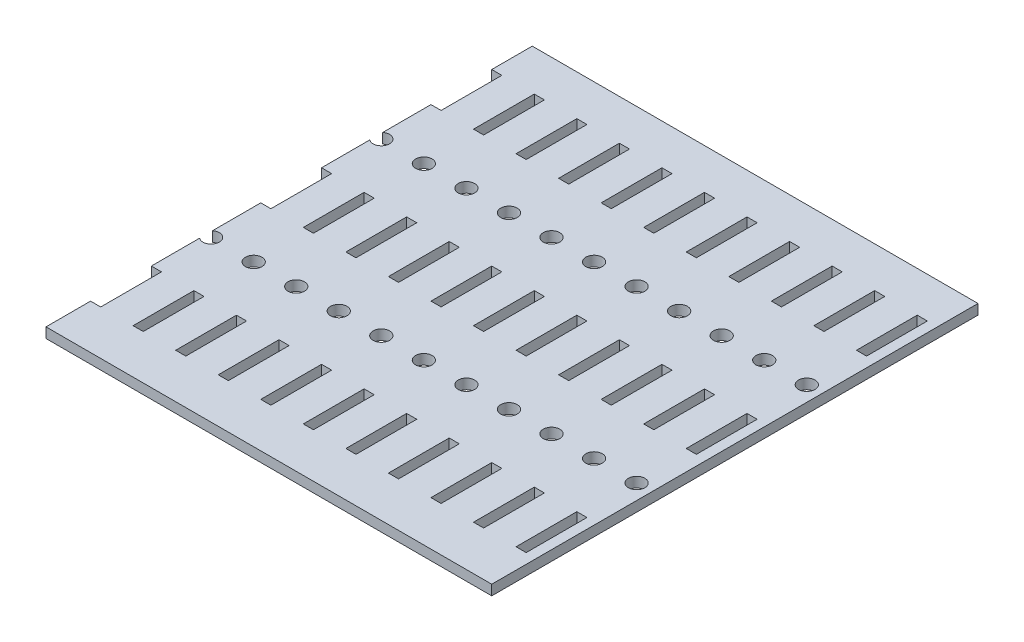
SolidWorks part; units mm, degrees
ref_plane "Front Plane" through (0, 0, 0) normal (0, 0, 1) x (1, 0, 0)
ref_plane "Top Plane" through (0, 0, 0) normal (0, 1, 0) x (1, 0, 0)
ref_plane "Right Plane" through (0, 0, 0) normal (1, 0, 0) x (0, 0, -1)
sketch "Sketch1" plane through (0, 0, 0) normal (0, 1, 0) x (1, 0, 0)
  line L1 (-79.7762, 84.4527) -> (59.9238, 84.4527)
  line L2 (-79.7762, 84.4527) -> (-79.7762, -67.9473)
  line L3 (-79.7762, -67.9473) -> (59.9238, -67.9473)
  line L4 (59.9238, 84.4527) -> (59.9238, -67.9473)
  dimension "D1" = 152.4
  dimension "D2" = 139.7
extrude "Boss-Extrude1" add sketch "Sketch1" along normal blind 3.175
sketch "Sketch2" plane through (0, 3.175, 0) normal (0, 1, 0) x (1, 0, 0)
  line L0 (59.9238, 84.4527) -> (-79.7762, 84.4527) construction
  line L1 (-79.7762, 71.7527) -> (-76.6012, 71.7527)
  line L2 (-79.7762, 71.7527) -> (-79.7762, 52.7027)
  line L3 (-79.7762, 52.7027) -> (-76.6012, 52.7027)
  line L4 (-76.6012, 71.7527) -> (-76.6012, 52.7027)
  line L5 (-79.7762, 18.4127) -> (-76.6012, 18.4127)
  line L6 (-79.7762, 18.4127) -> (-79.7762, -0.6373)
  line L7 (-79.7762, -0.6373) -> (-76.6012, -0.6373)
  line L8 (-76.6012, 18.4127) -> (-76.6012, -0.6373)
  line L9 (-79.7762, -34.9273) -> (-76.6012, -34.9273)
  line L10 (-79.7762, -34.9273) -> (-79.7762, -53.9773)
  line L11 (-79.7762, -53.9773) -> (-76.6012, -53.9773)
  line L12 (-76.6012, -34.9273) -> (-76.6012, -53.9773)
  line L14 (-79.7762, 84.4527) -> (-79.7762, -67.9473) construction
  dimension "D1" = 3.175
  dimension "D2" = 19.05
  dimension "D3" = 12.7
  dimension "D4" = 3
extrude "Cut-Extrude1" cut sketch "Sketch2" against normal through all
pattern_linear "LPattern1" count 11 spacing 13.335 along (1, 0, 0) of "Cut-Extrude1"
hole_wizard "13/64 (0.20313) Diameter Hole1" positions "Sketch4" profile "Sketch3" hole size "13/64" standard "ANSI Inch" end condition through all
sketch "Sketch4" plane through (0, 3.175, 0) normal (0, 1, 0) x (1, 0, 0)
  line L0 (55.1613, -34.9273) -> (55.1613, -0.6373) construction
  line L3 (41.8263, -34.9273) -> (41.8263, -0.6373) construction
  line L8 (43.4138, -34.9273) -> (40.2388, -34.9273) construction
  line L9 (56.7488, -34.9273) -> (53.5738, -34.9273) construction
  line L10 (53.5738, -0.6373) -> (56.7488, -0.6373) construction
  point P0 (55.1613, -17.7823)
  point P21 (41.8263, -17.7823)
  point P22 (28.4913, -17.7823)
  point P23 (15.1563, -17.7823)
  point P24 (1.8213, -17.7823)
  point P25 (-11.5137, -17.7823)
  point P26 (-24.8487, -17.7823)
  point P27 (-38.1837, -17.7823)
  point P28 (-51.5187, -17.7823)
  point P29 (-64.8537, -17.7823)
  point P30 (-78.1887, -17.7823)
  point P31 (-91.5237, -17.7823)
  point P32 (-104.8587, -17.7823)
  point P33 (-118.1937, -17.7823)
  point P34 (-131.5287, -17.7823)
  dimension "D1" = 15
sketch "Sketch3" plane through (55.1613, 3.175, 17.7823) normal (1, 0, 0) x (0, 0, 1)
  line L0 (0, 0) -> (0, 3.175)
  line L1 (0, 3.175) -> (2.5798, 3.175)
  line L2 (2.5798, 3.175) -> (2.5798, 0)
  line L5 (2.5798, 0) -> (0, 0)
  line L11 (0, -6.35) -> (0, 107.95) construction
  dimension "Thru Hole Dia." = 5.1595
  dimension "Thru Hole Depth" = 3.175
pattern_linear "LPattern2" count 2 spacing 53.34 along (0, 0, -1) of "13/64 (0.20313) Diameter Hole1"
